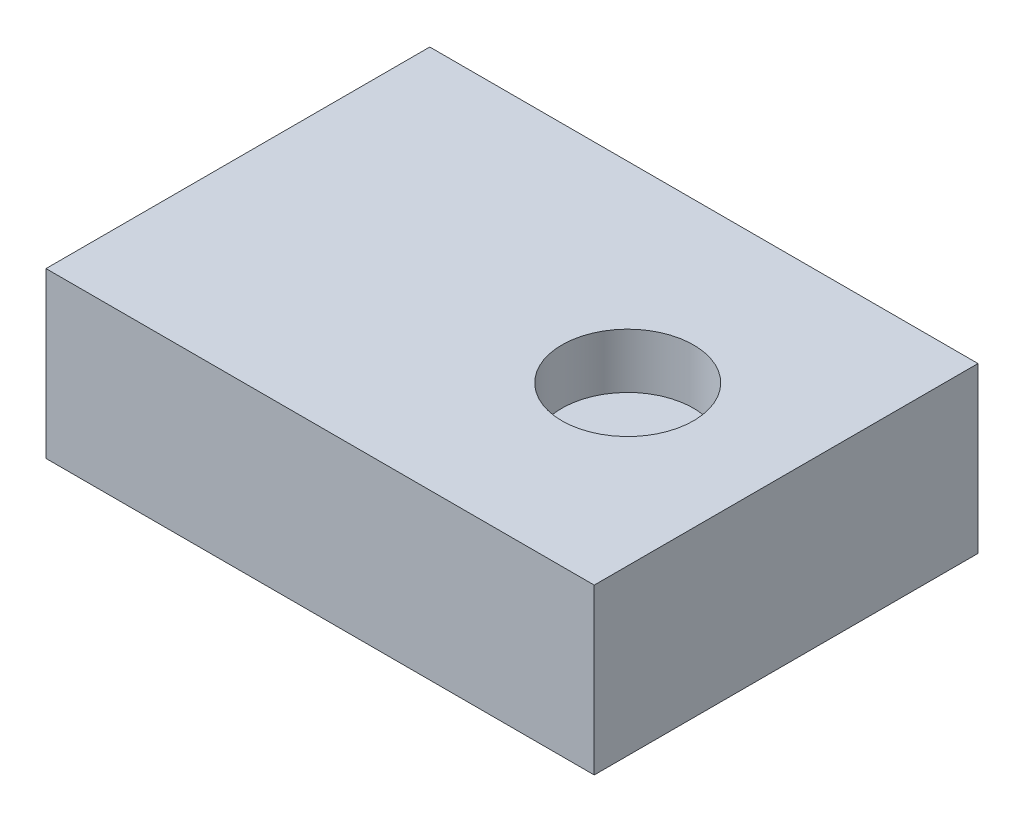
SolidWorks part; units mm, degrees
ref_plane "Спереди" through (0, 0, 0) normal (0, 0, 1) x (1, 0, 0)
ref_plane "Сверху" through (0, 0, 0) normal (0, 1, 0) x (1, 0, 0)
ref_plane "Справа" through (0, 0, 0) normal (1, 0, 0) x (0, 0, -1)
sketch "Эскиз1" plane through (0, 0, 0) normal (0, 1, 0) x (1, 0, 0)
  line L1 (-63.0679, 51.7292) -> (36.9321, 51.7292)
  line L2 (-63.0679, 51.7292) -> (-63.0679, -18.2708)
  line L3 (-63.0679, -18.2708) -> (36.9321, -18.2708)
  line L4 (36.9321, 51.7292) -> (36.9321, -18.2708)
extrude "Бобышка-Вытянуть1" add sketch "Эскиз1" along normal blind 30
sketch "Эскиз2" plane through (0, 30, 0) normal (0, 1, 0) x (1, 0, 0)
  line L0 (36.9321, 51.7292) -> (-63.0679, 51.7292) construction
  line L1 (-63.0679, -18.2708) -> (36.9321, -18.2708) construction
  circle A0 centre (8.0392, 16.7292) radius 12
  dimension "D1" = 35
  dimension "D2" = 35
extrude "Вырез-Вытянуть1" cut sketch "Эскиз2" against normal blind 10
